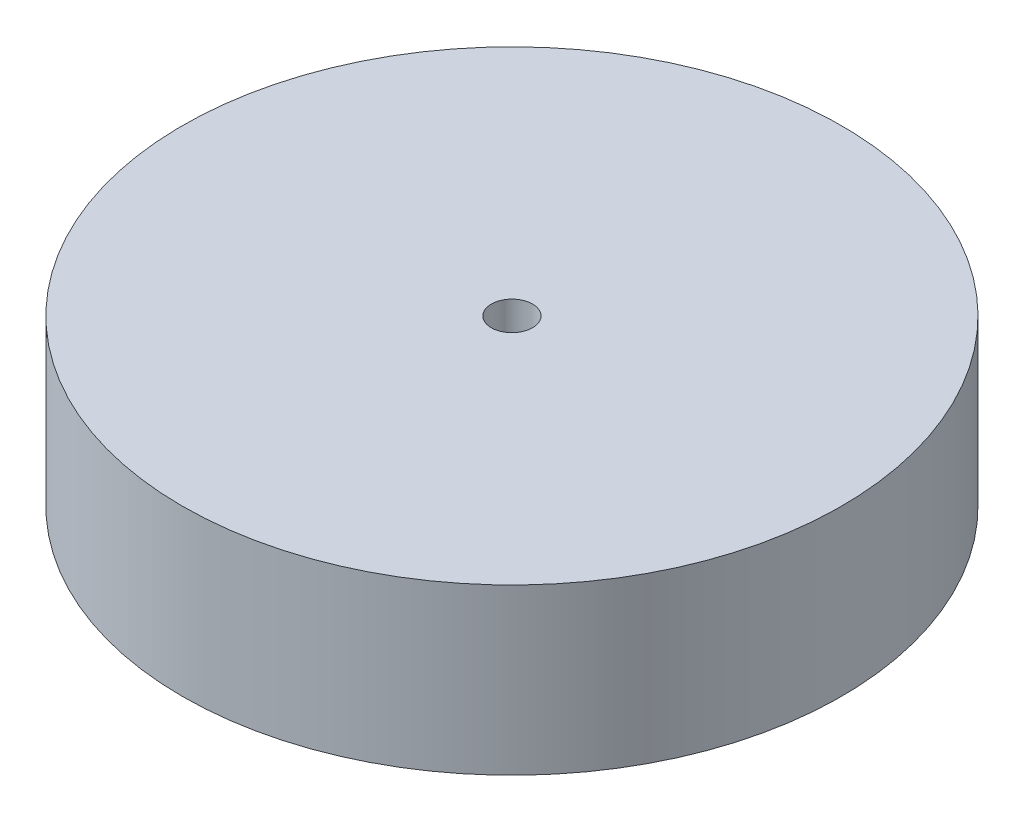
SolidWorks part; units mm, degrees
ref_plane "Front Plane" through (0, 0, 0) normal (0, 0, 1) x (1, 0, 0)
ref_plane "Top Plane" through (0, 0, 0) normal (0, 1, 0) x (1, 0, 0)
ref_plane "Right Plane" through (0, 0, 0) normal (1, 0, 0) x (0, 0, -1)
sketch "Sketch1" plane through (0, 0, 0) normal (0, 1, 0) x (1, 0, 0)
  circle A0 centre (0, 0) radius 63.5
  circle A1 centre (0, 0) radius 3.9688
  dimension "D1" = 127
  dimension "D2" = 7.9375
extrude "Boss-Extrude1" add sketch "Sketch1" along normal blind 31.75
